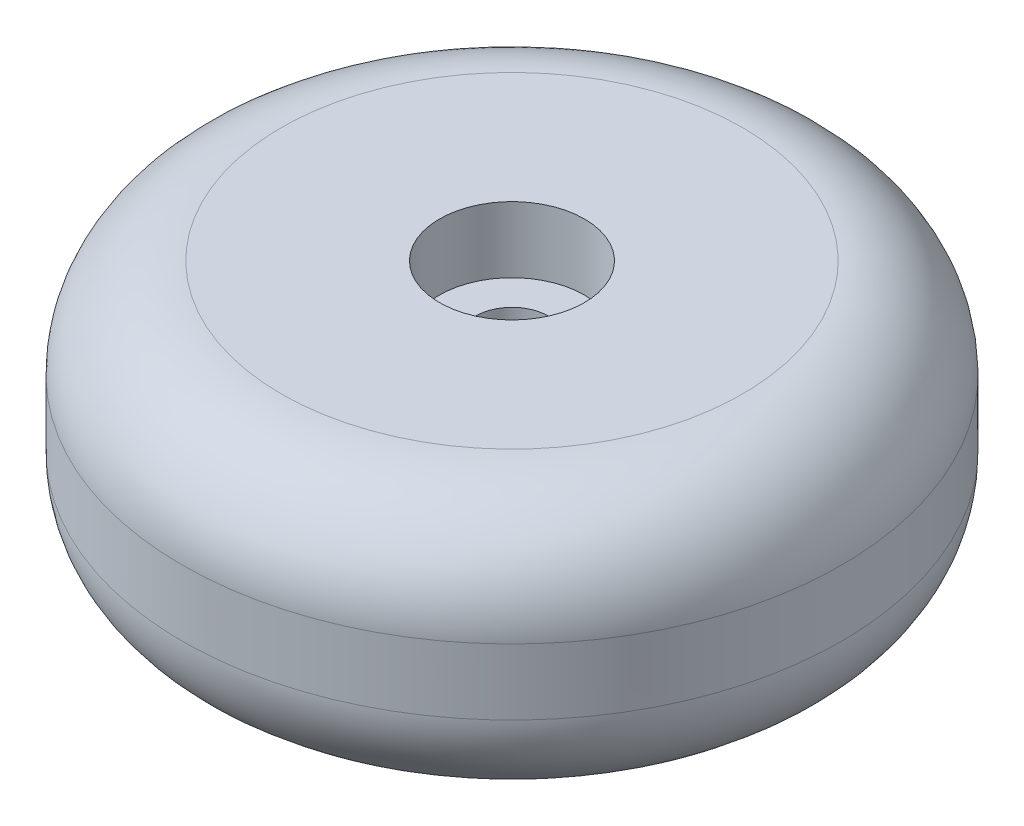
SolidWorks part; units mm, degrees
ref_plane "Front Plane" through (0, 0, 0) normal (0, 0, 1) x (1, 0, 0)
ref_plane "Top Plane" through (0, 0, 0) normal (0, 1, 0) x (1, 0, 0)
ref_plane "Right Plane" through (0, 0, 0) normal (1, 0, 0) x (0, 0, -1)
sketch "Sketch1" plane through (0, 0, 0) normal (0, 0, 1) x (1, 0, 0)
  line L0 (4.4, 16) -> (4.4, 12)
  line L1 (4.4, 12) -> (2.2, 12)
  line L2 (2.2, 12) -> (2.2, 0)
  line L3 (2.2, 0) -> (20, 0)
  line L4 (20, 0) -> (20, 16)
  line L5 (20, 16) -> (4.4, 16)
  line L6 (0, 0) -> (0, 37.8168) construction
  dimension "D1" = 2.2
  dimension "D2" = 4.4
  dimension "D3" = 20
  dimension "D4" = 4
  dimension "D5" = 12
revolve "Revolve1" add sketch "Sketch1" angle 360 about L6
fillet "Fillet1" radius 6 2 edges at (0, 0, -20) (0, 16, -20)
